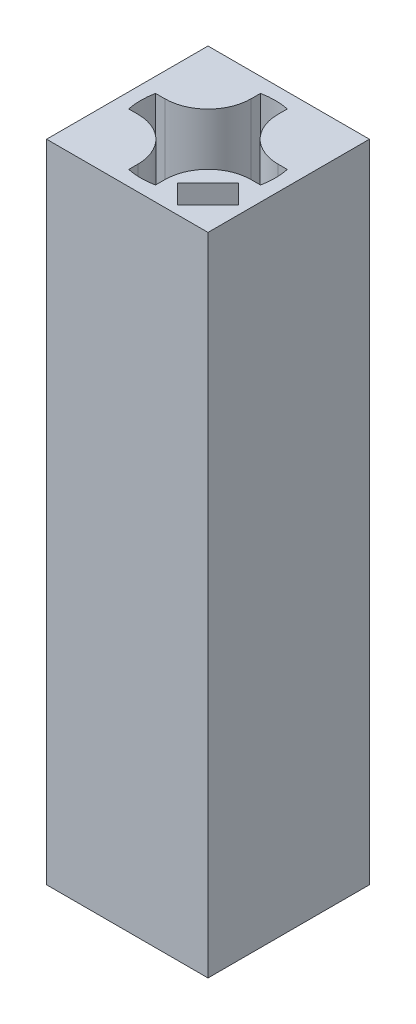
SolidWorks part; units mm, degrees
ref_plane "前视基准面" through (0, 0, 0) normal (0, 0, 1) x (1, 0, 0)
ref_plane "上视基准面" through (0, 0, 0) normal (0, 1, 0) x (1, 0, 0)
ref_plane "右视基准面" through (0, 0, 0) normal (1, 0, 0) x (0, 0, -1)
sketch "草图1" plane through (0, 0, 0) normal (0, 1, 0) x (1, 0, 0)
  line L1 (-15, -15) -> (15, -15)
  line L2 (-15, -15) -> (-15, 15)
  line L3 (-15, 15) -> (15, 15)
  line L4 (15, -15) -> (15, 15)
  line L5 (-15, -15) -> (15, 15) construction
  line L6 (-15, 15) -> (15, -15) construction
  point P0 (0, 0)
  dimension "D1" = 30
  dimension "D2" = 30
extrude "凸台-拉伸1" add sketch "草图1" along normal blind 120
sketch "草图2" plane through (0, 120, 0) normal (0, 1, 0) x (1, 0, 0)
  line L1 (-2.5, -12.2474) -> (2.5, -12.2474)
  line L2 (-2.5, -12.2474) -> (-2.5, 12.2474)
  line L3 (-2.5, 12.2474) -> (2.5, 12.2474)
  line L4 (2.5, -12.2474) -> (2.5, 12.2474)
  line L5 (-2.5, -12.2474) -> (2.5, 12.2474) construction
  line L6 (-2.5, 12.2474) -> (2.5, -12.2474) construction
  line L7 (-12.2474, -2.5) -> (12.2474, -2.5)
  line L8 (-12.2474, -2.5) -> (-12.2474, 2.5)
  line L9 (-12.2474, 2.5) -> (12.2474, 2.5)
  line L10 (12.2474, -2.5) -> (12.2474, 2.5)
  line L11 (-12.2474, -2.5) -> (12.2474, 2.5) construction
  line L12 (-12.2474, 2.5) -> (12.2474, -2.5) construction
  circle A0 centre (0, 0) radius 12.5
  dimension "D1" = 25
  dimension "D2" = 5
extrude "切除-拉伸1" cut sketch "草图2" against normal blind 100 contours L9 L8 L7 L2 | L9 L2 L7 L4 | L7 L2 L1 L4 | L7 L10 L9 L4 | L2 L9 L4 L3 | L8 A0 | L3 A0 | L10 A0 | L1 A0
fillet "圆角1" radius 8 4 edges at (-2.5, 70, 2.5) (2.5, 70, 2.5) (-2.5, 70, -2.5) (2.5, 70, -2.5)
sketch "草图4" plane through (0, 120, 0) normal (0, 1, 0) x (1, 0, 0)
  line L0 (0, 0) -> (15, -15) construction
  line L2 (4.2549, -9.9117) -> (9.9117, -4.2549)
  line L3 (4.2549, -9.9117) -> (7.7904, -13.4472)
  line L4 (9.9117, -4.2549) -> (13.4472, -7.7904)
  line L5 (7.7904, -13.4472) -> (13.4472, -7.7904)
  line L6 (4.2549, -9.9117) -> (13.4472, -7.7904) construction
  line L7 (9.9117, -4.2549) -> (7.7904, -13.4472) construction
  point P4 (7.1961, -7.1961)
  point P5 (8.0328, -8.0328)
  point P6 (8.8511, -8.8511)
  point P7 (8.8511, -8.8511)
  dimension "D1" = 8
  dimension "D2" = 5
extrude "切除-拉伸2" cut sketch "草图4" against normal blind 10
